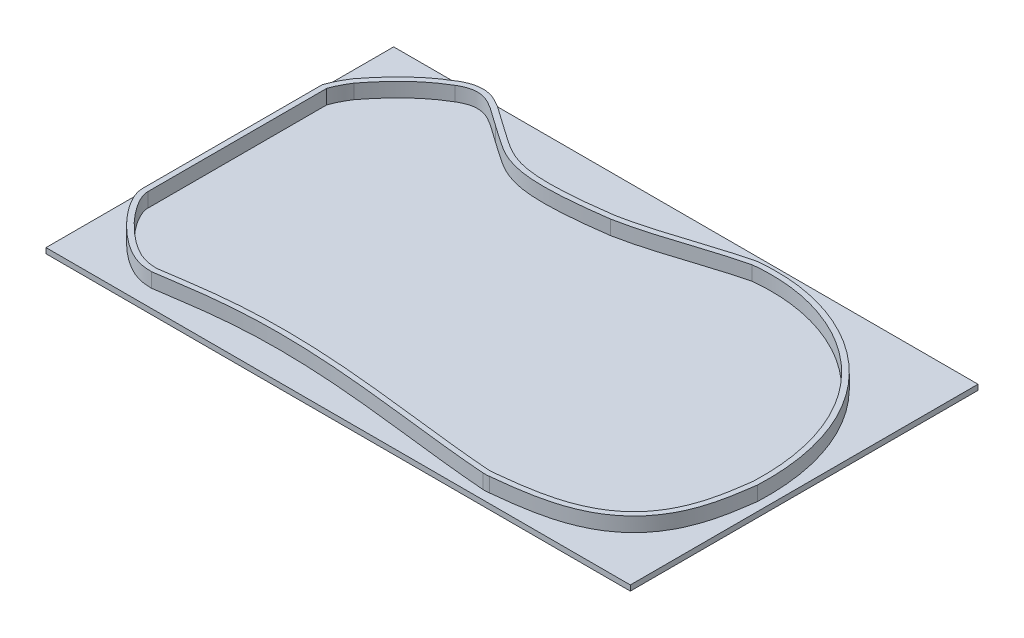
SolidWorks part; units mm, degrees
ref_plane "Front Plane" through (0, 0, 0) normal (0, 0, 1) x (1, 0, 0)
ref_plane "Top Plane" through (0, 0, 0) normal (0, 1, 0) x (1, 0, 0)
ref_plane "Right Plane" through (0, 0, 0) normal (1, 0, 0) x (0, 0, -1)
sketch "Sketch2" plane through (0, 0, 0) normal (0, 1, 0) x (1, 0, 0)
  line L1 (-78.1571, 35.933) -> (-78.1571, -14.1122)
  line L3 (-76.6571, 35.6791) -> (-76.6571, -14.1122)
  arc A1 (37.8695, -35.2975) -> (39.5975, -35.2134) centre (38.2635, -25.6055) ccw
  arc A2 (37.9543, -33.7997) -> (39.4138, -33.7244) centre (38.2635, -25.6055) ccw
  spline S0 degree 1 poles (-76.6571, -14.1122) (-56.9353, -31.4151) knots 0 0 1 1 construction
  spline S1 degree 1 poles (-56.9353, -31.4151) (37.9543, -33.7997) knots 0 0 1 1 construction
  spline S2 degree 1 poles (39.4138, -33.7244) (77.4865, 0.1985) knots 0 0 1 1 construction
  spline S3 degree 1 poles (77.4865, 0.1985) (25.1467, 52.3798) knots 0 0 1 1 construction
  spline S4 degree 1 poles (25.1467, 52.3798) (-5.5776, 43.6969) knots 0 0 1 1 construction
  spline S5 degree 1 poles (-5.5776, 43.6969) (-44.2667, 50.2753) knots 0 0 1 1 construction
  spline S6 degree 1 poles (-44.2667, 50.2753) (-59.5151, 54.2938) knots 0 0 1 1 construction
  spline S7 degree 1 poles (-59.5151, 54.2938) (-74.1103, 40.7589) knots 0 0 1 1 construction
  spline S8 degree 1 poles (-74.1103, 40.7589) (-76.6571, 35.6791) knots 0 0 1 1 construction
  spline S9 degree 3 poles (-76.6571, -14.1122) (-76.6565, -14.3409) (-76.6155, -14.7806) (-76.3656, -15.7796) (-75.747, -17.2613) (-74.6379, -19.1243) (-72.785, -21.6665) (-70.0272, -24.6961) (-66.6025, -27.6727) (-63.4769, -29.756) (-60.8742, -30.9164) (-58.8235, -31.3434) (-57.5751, -31.3793) (-56.9353, -31.4151) knots 0.000537 0.000537 0.000537 0.000537 0.031486 0.062436 0.124334 0.186233 0.248131 0.371928 0.495725 0.619522 0.743319 0.867116 0.990913 0.990913 0.990913 0.990913
  spline S10 degree 3 poles (-56.9353, -31.4151) (-56.6947, -31.3857) (-56.2236, -31.3259) (-55.2035, -31.1853) (-53.8563, -30.9861) (-52.1019, -30.7165) (-49.5965, -30.3331) (-46.1596, -29.8344) (-41.5816, -29.2783) (-36.5815, -28.8235) (-29.3907, -28.4116) (-19.4979, -28.3481) (-6.4075, -29.0922) (7.6711, -30.5324) (20.0455, -32.036) (30.2038, -33.1444) (35.3757, -33.6086) (37.9543, -33.7997) knots 0.001496 0.001496 0.001496 0.001496 0.017094 0.032692 0.063887 0.095082 0.126278 0.188669 0.25106 0.313451 0.375842 0.500623 0.625405 0.750187 0.874969 0.93736 0.999751 0.999751 0.999751 0.999751
  spline S11 degree 3 poles (39.4138, -33.7244) (40.9416, -33.5617) (44.0169, -33.2198) (49.9744, -32.3539) (56.9206, -30.7137) (63.9289, -27.4671) (69.3764, -22.8718) (72.5925, -18.0666) (74.4353, -13.8863) (75.4874, -10.6778) (76.2524, -7.5122) (76.6995, -5.0231) (76.9794, -3.1938) (77.1604, -1.9321) (77.3268, -0.7681) (77.4312, -0.1354) (77.4865, 0.1985) knots -0.000425 -0.000425 -0.000425 -0.000425 0.062921 0.126267 0.25296 0.379652 0.506344 0.633037 0.696383 0.759729 0.823075 0.886421 0.918094 0.949767 0.98144 1.013113 1.013113 1.013113 1.013113
  spline S12 degree 3 poles (77.4865, 0.1985) (77.5294, 1.305) (77.5631, 3.5464) (77.4417, 6.7504) (77.16, 9.8693) (76.5779, 13.8919) (75.4769, 18.6588) (72.9828, 25.7335) (68.609, 33.5174) (61.7183, 41.1126) (53.553, 46.8991) (44.4782, 50.8084) (34.8789, 52.7763) (28.3613, 52.736) (25.1467, 52.3798) knots 0.000462 0.000462 0.000462 0.000462 0.031685 0.062907 0.09413 0.125353 0.187798 0.250243 0.375133 0.500024 0.624914 0.749804 0.874695 0.999585 0.999585 0.999585 0.999585
  spline S13 degree 3 poles (25.1467, 52.3798) (19.9969, 51.1378) (12.4631, 48.6515) (2.2829, 45.4856) (-2.9435, 44.2002) (-5.5776, 43.6969) knots 0.001648 0.001648 0.001648 0.001648 0.498756 0.74731 0.995864 0.995864 0.995864 0.995864
  spline S14 degree 3 poles (-5.5776, 43.6969) (-6.6087, 43.5524) (-8.654, 43.2773) (-12.9007, 42.7706) (-18.1416, 42.2965) (-23.9011, 42.1313) (-28.8945, 42.4918) (-33.1236, 43.4728) (-36.1527, 44.8486) (-38.4697, 46.2593) (-40.2278, 47.4575) (-41.798, 48.5733) (-43.1496, 49.5189) (-43.8992, 50.0282) (-44.2667, 50.2753) knots -0.000446 -0.000446 -0.000446 -0.000446 0.062357 0.12516 0.250765 0.376371 0.501977 0.627582 0.753188 0.815991 0.878794 0.941597 0.972998 1.004399 1.004399 1.004399 1.004399
  spline S15 degree 3 poles (-44.2667, 50.2753) (-44.5274, 50.4551) (-45.0542, 50.8224) (-46.0418, 51.5266) (-47.1829, 52.3529) (-48.4305, 53.2384) (-49.9594, 54.2549) (-51.669, 55.1907) (-53.504, 55.7629) (-55.2171, 55.8536) (-56.8628, 55.5425) (-58.1189, 55.0484) (-58.9919, 54.6028) (-59.3349, 54.4021) (-59.5151, 54.2938) knots -0.002599 -0.002599 -0.002599 -0.002599 0.028976 0.060551 0.123702 0.186852 0.250002 0.376303 0.502603 0.628904 0.755204 0.881505 0.944655 1.007805 1.007805 1.007805 1.007805
  spline S16 degree 3 poles (-78.1571, -14.1122) (-78.1559, -14.7524) (-77.9173, -15.9777) (-77.0678, -17.9828) (-75.8538, -20.0098) (-73.8827, -22.6985) (-70.9901, -25.8584) (-67.4096, -28.9504) (-64.0991, -31.1349) (-61.2379, -32.3904) (-59.243, -32.7789) (-57.8421, -32.8756) (-57.2118, -32.9007) (-56.8882, -32.9203) knots 0.000409 0.000409 0.000409 0.000409 0.062843 0.125276 0.18771 0.250143 0.375011 0.499878 0.624745 0.749612 0.874479 0.936913 0.999346 0.999346 0.999346 0.999346
  spline S17 degree 3 poles (-56.8882, -32.9203) (-56.6427, -32.8908) (-56.1603, -32.8306) (-55.1309, -32.6904) (-53.7754, -32.491) (-52.0233, -32.2221) (-49.5292, -31.8398) (-46.1189, -31.3427) (-41.5829, -30.7872) (-36.6286, -30.3313) (-29.4997, -29.9158) (-19.6749, -29.8441) (-6.6369, -30.5782) (5.0856, -31.7749) (14.8757, -32.919) (22.3927, -33.8009) (30.0532, -34.6371) (35.2704, -35.1052) (37.8695, -35.2975) knots -0.001373 -0.001373 -0.001373 -0.001373 0.014273 0.029919 0.06121 0.092502 0.123794 0.186377 0.24896 0.311543 0.374127 0.499293 0.62446 0.749626 0.81221 0.874793 0.937376 0.99996 0.99996 0.99996 0.99996
  spline S18 degree 3 poles (39.5975, -35.2134) (41.1398, -35.049) (44.2356, -34.7045) (50.3018, -33.8209) (57.4502, -32.1301) (64.7991, -28.7164) (70.5782, -23.8111) (73.9656, -18.7006) (75.8832, -14.3057) (76.9672, -10.962) (77.7479, -7.6914) (78.1997, -5.145) (78.4804, -3.2966) (78.6613, -2.0308) (78.824, -0.9009) (78.9276, -0.2806) (78.9816, 0.0458) knots -0.000086 -0.000086 -0.000086 -0.000086 0.063428 0.126941 0.253967 0.380993 0.50802 0.635046 0.698559 0.762072 0.825585 0.889098 0.920855 0.952612 0.984368 1.016125 1.016125 1.016125 1.016125
  spline S19 degree 3 poles (78.9816, 0.0458) (79.0271, 1.1797) (79.0647, 3.4739) (78.9444, 6.7697) (78.6587, 9.9749) (78.0642, 14.1169) (76.9341, 19.0326) (74.3646, 26.3398) (69.8439, 34.3944) (62.712, 42.2543) (54.2626, 48.2351) (44.8799, 52.2671) (34.9529, 54.2886) (28.2109, 54.2351) (24.8869, 53.8601) knots -0.000407 -0.000407 -0.000407 -0.000407 0.03088 0.062166 0.093453 0.12474 0.187314 0.249888 0.375035 0.500183 0.62533 0.750478 0.875625 1.000773 1.000773 1.000773 1.000773
  spline S20 degree 3 poles (24.8869, 53.8601) (22.2839, 53.2349) (17.1223, 51.77) (6.9788, 48.4835) (-0.6206, 46.1711) (-5.8226, 45.1772) knots -0.001281 -0.001281 -0.001281 -0.001281 0.247714 0.49671 0.9947 0.9947 0.9947 0.9947
  spline S21 degree 3 poles (-5.8226, 45.1772) (-6.8463, 45.0337) (-8.8779, 44.761) (-13.0882, 44.2593) (-18.2643, 43.7927) (-23.9018, 43.6338) (-28.7026, 43.9859) (-32.6523, 44.9085) (-35.4477, 46.177) (-37.6484, 47.5152) (-39.3619, 48.6824) (-40.9248, 49.793) (-42.292, 50.7496) (-43.0505, 51.2651) (-43.4225, 51.5151) knots 0.000305 0.000305 0.000305 0.000305 0.063048 0.125791 0.251276 0.376761 0.502247 0.627732 0.753218 0.815961 0.878703 0.941446 0.972817 1.004189 1.004189 1.004189 1.004189
  spline S22 degree 3 poles (-43.4225, 51.5151) (-43.6786, 51.6918) (-44.1958, 52.0526) (-45.1684, 52.7462) (-46.308, 53.5714) (-47.577, 54.4721) (-49.1727, 55.5335) (-51.0441, 56.5648) (-53.2147, 57.2519) (-55.3195, 57.3652) (-56.9568, 57.0533) (-58.1477, 56.6506) (-58.9689, 56.2985) (-59.5708, 55.992) (-60.0059, 55.7483) (-60.1862, 55.6406) (-60.2803, 55.5839) knots -0.002294 -0.002294 -0.002294 -0.002294 0.029245 0.060783 0.12386 0.186936 0.250013 0.376167 0.50232 0.628473 0.754627 0.817704 0.88078 0.943857 0.975396 1.006934 1.006934 1.006934 1.006934
  spline S23 degree 3 poles (-60.2803, 55.5839) (-60.715, 55.3297) (-61.582, 54.801) (-63.2222, 53.7187) (-65.9105, 51.7373) (-69.2431, 48.741) (-72.0244, 45.6929) (-73.7392, 43.6279) (-74.6657, 42.4756) (-75.1049, 41.9202) (-75.3265, 41.639) knots 0.000427 0.000427 0.000427 0.000427 0.063268 0.126109 0.251792 0.503158 0.754524 0.880206 0.943048 1.005889 1.005889 1.005889 1.005889
  spline S24 degree 3 poles (-59.5151, 54.2938) (-59.933, 54.0493) (-60.7671, 53.5412) (-62.3441, 52.5014) (-64.933, 50.5956) (-68.1535, 47.7049) (-70.8563, 44.7494) (-72.7891, 42.425) (-73.6662, 41.3222) (-74.1103, 40.7589) knots 0.000048 0.000048 0.000048 0.000048 0.062687 0.125326 0.250603 0.501159 0.751715 0.876992 1.00227 1.00227 1.00227 1.00227
  spline S25 degree 3 poles (-74.1103, 40.7589) (-74.6386, 39.9596) (-75.6117, 38.2814) (-76.343, 36.5646) (-76.6571, 35.6791) knots 0.499551 0.499551 0.499551 0.499551 0.499763 0.499976 0.499976 0.499976 0.499976
  spline S26 degree 3 poles (-75.3265, 41.639) (-75.92, 40.746) (-77.0064, 38.8701) (-77.815, 36.9314) (-78.1571, 35.933) knots 0.499546 0.499546 0.499546 0.499546 0.49977 0.499995 0.499995 0.499995 0.499995
  point P0 (0.4631, 0.0343)
  dimension "D1" = 1.5
extrude "Boss-Extrude2" add sketch "Sketch2" along normal blind 4
sketch "Sketch3" plane through (0, 0, 0) normal (0, -1, 0) x (1, 0, 0)
  line L1 (-81.3379, 37.7967) -> (81.3759, 37.7967)
  line L2 (-81.3379, 37.7967) -> (-81.3379, -59.0189)
  line L3 (-81.3379, -59.0189) -> (81.3759, -59.0189)
  line L4 (81.3759, 37.7967) -> (81.3759, -59.0189)
extrude "Boss-Extrude3" add sketch "Sketch3" along normal blind 1.5
